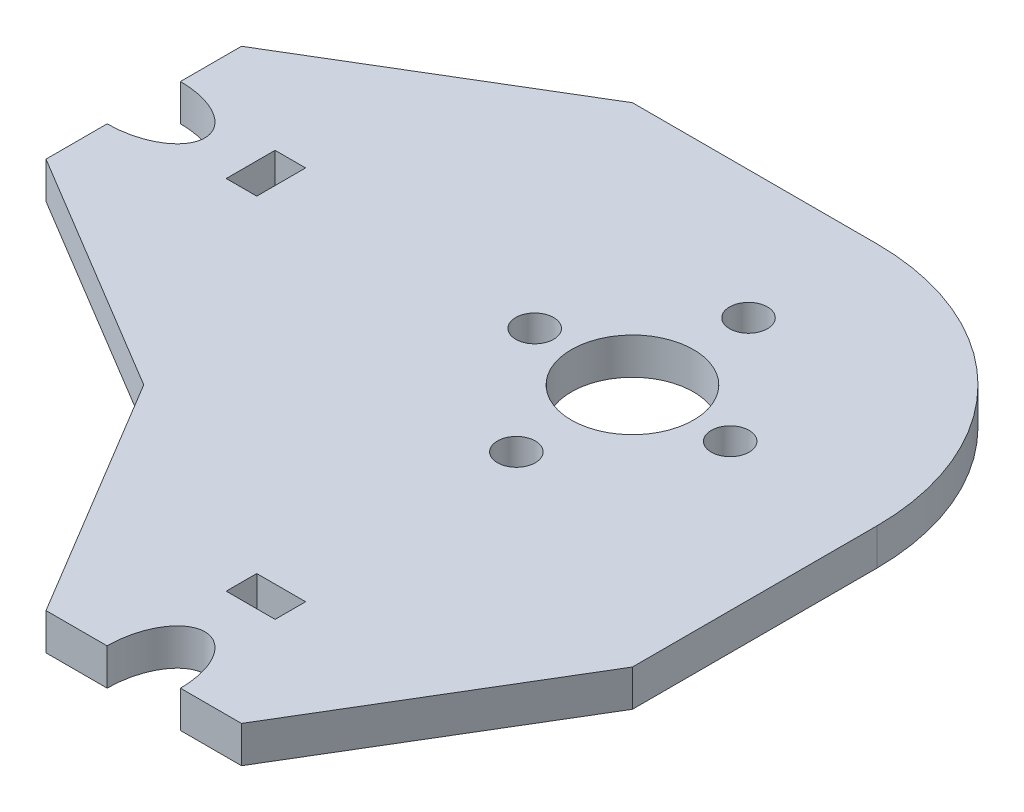
SolidWorks part; units mm, degrees
ref_plane "前基準面" through (0, 0, 0) normal (0, 0, 1) x (1, 0, 0)
ref_plane "上基準面" through (0, 0, 0) normal (0, 1, 0) x (1, 0, 0)
ref_plane "右基準面" through (0, 0, 0) normal (1, 0, 0) x (0, 0, -1)
sketch "草圖2" plane through (0, 0, 0) normal (0, 1, 0) x (1, 0, 0)
  line L0 (0, 0) -> (-68.5512, 0) construction
  line L1 (-40, 3) -> (-40, 8)
  line L2 (-40, 8) -> (-20, 20)
  line L3 (-20, 20) -> (0, 20)
  line L4 (-20, 20.9065) -> (-20, -20) construction
  line L5 (-40, -3) -> (-40, -8)
  line L6 (-40, -8) -> (-20, -20)
  line L8 (0, 0) -> (-30.1479, -30.1479) construction
  line L9 (-20, -20) -> (0, -20) construction
  line L10 (-40, 8) -> (-20, 20)
  line L11 (-40, 3) -> (-40, 8)
  line L12 (-40, -8) -> (-20, -20)
  line L13 (-40, -3) -> (-40, -8)
  line L14 (3, -40) -> (8, -40)
  line L15 (-8, -40) -> (-20, -20)
  line L16 (-3, -40) -> (-8, -40)
  line L17 (8, -40) -> (20, -20)
  line L18 (20, -20) -> (20, 0)
  line L19 (0, 0) -> (33.8301, 0) construction
  line L20 (0, 0) -> (0, -16.5032) construction
  line L21 (-2, -28.75) -> (2, -28.75)
  line L22 (-31.25, -2) -> (-28.75, -2)
  line L23 (-31.25, -2) -> (-31.25, 2)
  line L24 (-31.25, 2) -> (-28.75, 2)
  line L25 (-28.75, -2) -> (-28.75, 2)
  line L26 (-31.25, -2) -> (-28.75, 2) construction
  line L27 (-31.25, 2) -> (-28.75, -2) construction
  line L28 (-2, -31.25) -> (-2, -28.75)
  line L29 (-2, -31.25) -> (2, -31.25)
  line L30 (2, -31.25) -> (2, -28.75)
  circle A0 centre (0, 0) radius 20 construction
  arc A1 (0, 20) -> (20, 0) centre (0, 0) cw
  circle A2 centre (0, 0) radius 5
  circle A3 centre (8, 0) radius 1.55
  circle A4 centre (0, -9.5) radius 1.55
  circle A5 centre (-8, 0) radius 1.55
  circle A6 centre (0, 9.5) radius 1.55
  ellipse E0 centre (-40, 0) end of major axis (-35, 0) minor radius 3 (-40, -3) -> (-40, 3) ccw
  ellipse E1 centre (0, -40) end of major axis (0, -45) minor radius 3 (-3, -40) -> (3, -40) cw
  point P44 (-30, 0)
  dimension "D1" = 40
  dimension "D5" = 3.1
  dimension "D6" = 10
  dimension "D7" = 8
  dimension "D2" = 40
  dimension "D3" = 5
  dimension "D4" = 45
  dimension "D8" = 9.5
  dimension "D9" = 2.5
  dimension "D10" = 4
  dimension "D11" = 10
extrude "填料-伸長1" add sketch "草圖2" along normal blind 3 contours L16 E1 L14 L17 L18 A1 L3 L2 L1 E0 L5 L6 L15 A6 A2 A3 A4 A5
